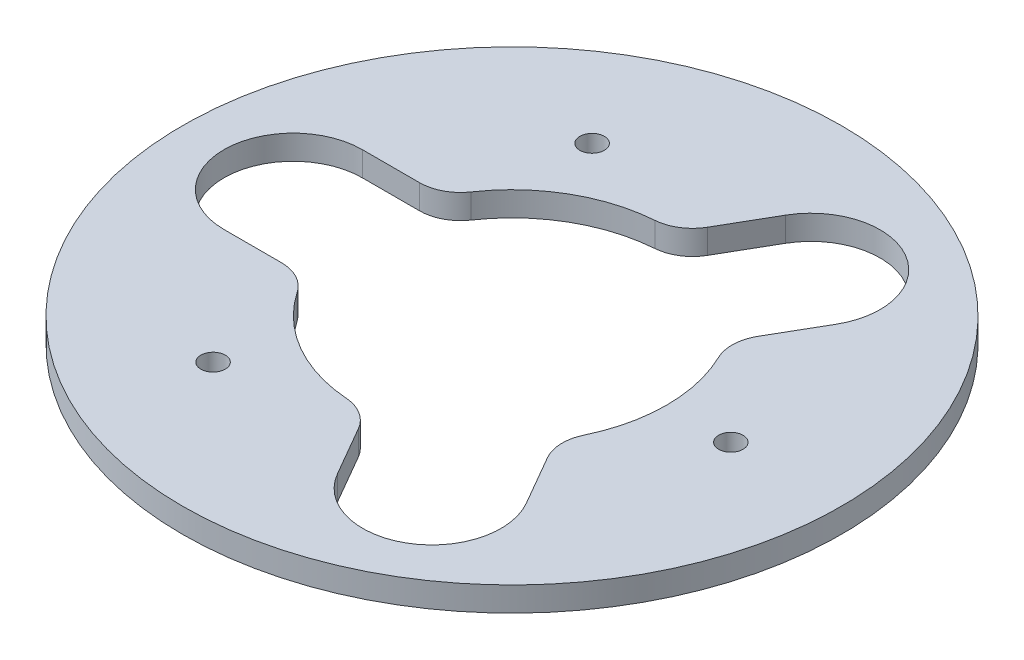
SolidWorks part; units mm, degrees
ref_plane "Front Plane" through (0, 0, 0) normal (0, 0, 1) x (1, 0, 0)
ref_plane "Top Plane" through (0, 0, 0) normal (0, 1, 0) x (1, 0, 0)
ref_plane "Right Plane" through (0, 0, 0) normal (1, 0, 0) x (0, 0, -1)
other "Graphic1"
other "Graphic (Closed) -1"
sketch "Sketch1" plane through (0, 0, 0) normal (0, 1, 0) x (1, 0, 0)
  line L0 (6.0858, 27.541) -> (2.5604, 21.4347)
  line L1 (-26.8941, 8.5) -> (-19.8431, 8.5)
  line L2 (-26.8941, -8.5) -> (-19.8431, -8.5)
  line L3 (20.8083, 19.041) -> (17.2828, 12.9347)
  line L4 (20.8083, -19.041) -> (17.2828, -12.9347)
  line L5 (6.0858, -27.541) -> (2.5604, -21.4347)
  line L6 (-14.7461, 22.541) -> (-12.148, 24.041) construction
  circle A0 centre (0, 0) radius 40.5
  arc A1 (-15.7091, -10.6875) -> (-1.4011, -18.9483) centre (0, 0) ccw
  arc A2 (-26.8941, 8.5) -> (-26.8941, -8.5) centre (-26.8941, 0) ccw
  arc A3 (-19.8431, -8.5) -> (-15.7091, -10.6875) centre (-19.8431, -13.5) cw
  arc A4 (-19.8431, 8.5) -> (-15.7091, 10.6875) centre (-19.8431, 13.5) ccw
  arc A5 (17.2828, 12.9347) -> (17.1102, 8.2608) centre (21.6129, 10.4347) ccw
  arc A6 (2.5604, 21.4347) -> (-1.4011, 18.9483) centre (-1.7698, 23.9347) cw
  arc A7 (20.8083, 19.041) -> (6.0858, 27.541) centre (13.4471, 23.291) ccw
  arc A8 (2.5604, -21.4347) -> (-1.4011, -18.9483) centre (-1.7698, -23.9347) ccw
  arc A9 (17.2828, -12.9347) -> (17.1102, -8.2608) centre (21.6129, -10.4347) cw
  arc A10 (6.0858, -27.541) -> (20.8083, -19.041) centre (13.4471, -23.291) ccw
  arc A11 (-1.4011, 18.9483) -> (-15.7091, 10.6875) centre (0, 0) ccw
  arc A12 (17.1102, -8.2608) -> (17.1102, 8.2608) centre (0, 0) ccw
  circle A13 centre (-13.4471, 23.291) radius 1.5
  circle A14 centre (26.8941, 0) radius 1.5
  circle A15 centre (-13.4471, -23.291) radius 1.5
  point P34 (0, 0)
  point P45 (0, 0)
  dimension "D1" = 5
  dimension "D3" = 3
  dimension "D2" = 3
extrude "Boss-Extrude1" add sketch "Sketch1" against normal blind 3
